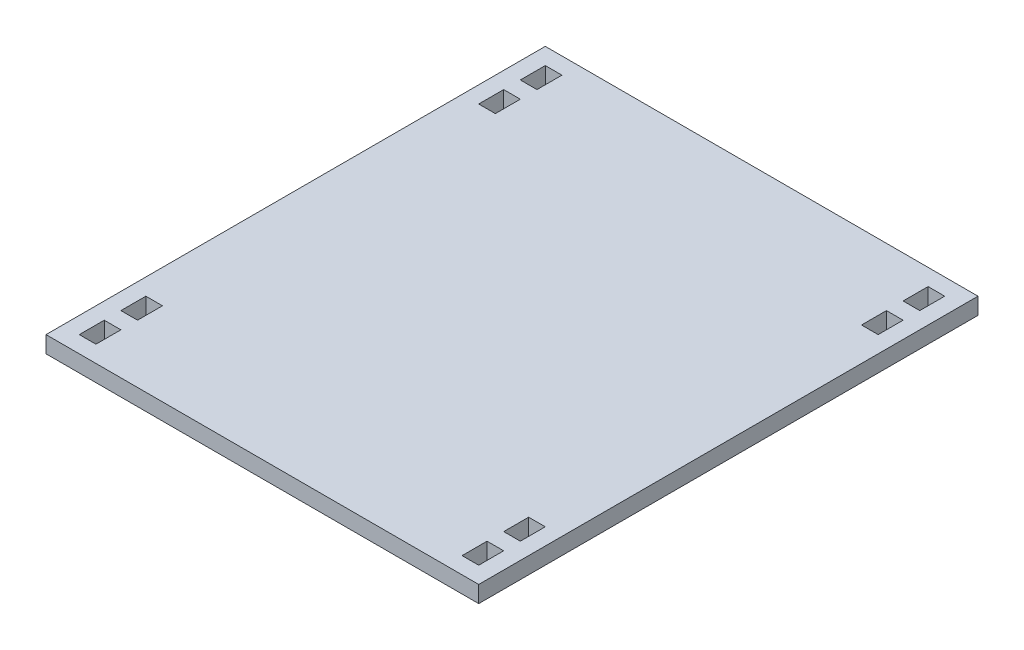
SolidWorks part; units mm, degrees
ref_plane "Front Plane" through (0, 0, 0) normal (0, 0, 1) x (1, 0, 0)
ref_plane "Top Plane" through (0, 0, 0) normal (0, 1, 0) x (1, 0, 0)
ref_plane "Right Plane" through (0, 0, 0) normal (1, 0, 0) x (0, 0, -1)
sketch "Sketch1" plane through (0, 0, 0) normal (0, 1, 0) x (1, 0, 0)
  line L1 (41.275, -47.625) -> (-41.275, -47.625)
  line L2 (41.275, -47.625) -> (41.275, 47.625)
  line L3 (41.275, 47.625) -> (-41.275, 47.625)
  line L4 (-41.275, -47.625) -> (-41.275, 47.625)
  line L5 (41.275, -47.625) -> (-41.275, 47.625) construction
  line L6 (41.275, 47.625) -> (-41.275, -47.625) construction
  point P0 (0, 0)
  dimension "D1" = 82.55
  dimension "D2" = 95.25
extrude "Boss-Extrude1" add sketch "Sketch1" along normal blind 3.175
sketch "Sketch2" plane through (0, 3.175, 0) normal (0, 1, 0) x (1, 0, 0)
  line L0 (-38.1, 39.6875) -> (-38.1, 44.45)
  line L1 (-34.925, 36.5125) -> (-38.1, 36.5125)
  line L2 (-34.925, 36.5125) -> (-34.925, 39.6875) construction
  line L3 (-34.925, 39.6875) -> (-38.1, 39.6875)
  line L4 (-38.1, 36.5125) -> (-38.1, 39.6875) construction
  line L5 (-34.925, 36.5125) -> (-38.1, 39.6875) construction
  line L6 (-34.925, 39.6875) -> (-38.1, 36.5125) construction
  line L7 (-38.1, 44.45) -> (-34.925, 44.45)
  line L8 (-34.925, 44.45) -> (-34.925, 39.6875)
  line L9 (-34.925, 36.5125) -> (-34.925, 31.75)
  line L10 (-34.925, 31.75) -> (-38.1, 31.75)
  line L11 (-38.1, 31.75) -> (-38.1, 36.5125)
  line L12 (-41.275, 47.625) -> (-41.275, -47.625) construction
  line L13 (41.275, 47.625) -> (-41.275, 47.625) construction
  point P0 (-36.5125, 38.1)
  dimension "D1" = 3.175
  dimension "D2" = 3.175
  dimension "D3" = 4.7625
  dimension "D4" = 3.175
  dimension "D5" = 3.175
extrude "Cut-Extrude1" cut sketch "Sketch2" against normal through all contours L11 L1 L9 L10 | L8 L3 L0 L7
pattern_linear "LPattern1" count 2 spacing 76.2 along (0, 0, 1) count 2 spacing 73.025 along (1, 0, 0) of "Cut-Extrude1"
sketch "Sketch3" plane through (0, 0, 0) normal (0, -1, 0) x (1, 0, 0)
  line L8 (-41.3512, 47.7012) -> (-41.3512, -47.7012)
  line L9 (-41.3512, -47.7012) -> (41.3512, -47.7012)
  line L10 (41.3512, -47.7012) -> (41.3512, 47.7012)
  line L11 (41.3512, 47.7012) -> (-41.3512, 47.7012)
  line L12 (-41.3512, 47.7012) -> (-41.3512, -47.7012)
  line L13 (-41.3512, -47.7012) -> (41.3512, -47.7012)
  line L14 (41.3512, -47.7012) -> (41.3512, 47.7012)
  line L15 (41.3512, 47.7012) -> (-41.3512, 47.7012)
  line L20 (35.0012, -36.4363) -> (38.0238, -36.4363)
  line L21 (35.0012, -31.8262) -> (35.0012, -36.4363)
  line L22 (38.0238, -31.8262) -> (35.0012, -31.8262)
  line L23 (38.0238, -36.4363) -> (38.0238, -31.8262)
  line L24 (35.0012, -36.4363) -> (38.0238, -36.4363)
  line L25 (35.0012, -31.8262) -> (35.0012, -36.4363)
  line L26 (38.0238, -31.8262) -> (35.0012, -31.8262)
  line L27 (38.0238, -36.4363) -> (38.0238, -31.8262)
  line L32 (35.0012, -44.3738) -> (38.0238, -44.3738)
  line L33 (38.0238, -44.3738) -> (38.0238, -39.7637)
  line L34 (38.0238, -39.7637) -> (35.0012, -39.7637)
  line L35 (35.0012, -39.7637) -> (35.0012, -44.3738)
  line L36 (35.0012, -44.3738) -> (38.0238, -44.3738)
  line L37 (38.0238, -44.3738) -> (38.0238, -39.7637)
  line L38 (38.0238, -39.7637) -> (35.0012, -39.7637)
  line L39 (35.0012, -39.7637) -> (35.0012, -44.3738)
  line L44 (35.0012, 39.7637) -> (38.0238, 39.7637)
  line L45 (38.0238, 39.7637) -> (38.0238, 44.3738)
  line L46 (38.0238, 44.3738) -> (35.0012, 44.3738)
  line L47 (35.0012, 44.3738) -> (35.0012, 39.7637)
  line L48 (35.0012, 39.7637) -> (38.0238, 39.7637)
  line L49 (38.0238, 39.7637) -> (38.0238, 44.3738)
  line L50 (38.0238, 44.3738) -> (35.0012, 44.3738)
  line L51 (35.0012, 44.3738) -> (35.0012, 39.7637)
  line L56 (35.0012, 31.8262) -> (38.0238, 31.8262)
  line L57 (35.0012, 36.4363) -> (35.0012, 31.8262)
  line L58 (38.0238, 36.4363) -> (35.0012, 36.4363)
  line L59 (38.0238, 31.8262) -> (38.0238, 36.4363)
  line L60 (35.0012, 31.8262) -> (38.0238, 31.8262)
  line L61 (35.0012, 36.4363) -> (35.0012, 31.8262)
  line L62 (38.0238, 36.4363) -> (35.0012, 36.4363)
  line L63 (38.0238, 31.8262) -> (38.0238, 36.4363)
  line L68 (-35.0012, -31.8262) -> (-38.0238, -31.8262)
  line L69 (-35.0012, -36.4363) -> (-35.0012, -31.8262)
  line L70 (-38.0238, -36.4363) -> (-35.0012, -36.4363)
  line L71 (-38.0238, -31.8262) -> (-38.0238, -36.4363)
  line L72 (-35.0012, -31.8262) -> (-38.0238, -31.8262)
  line L73 (-35.0012, -36.4363) -> (-35.0012, -31.8262)
  line L74 (-38.0238, -36.4363) -> (-35.0012, -36.4363)
  line L75 (-38.0238, -31.8262) -> (-38.0238, -36.4363)
  line L80 (-38.0238, -44.3738) -> (-35.0012, -44.3738)
  line L81 (-35.0012, -44.3738) -> (-35.0012, -39.7637)
  line L82 (-35.0012, -39.7637) -> (-38.0238, -39.7637)
  line L83 (-38.0238, -39.7637) -> (-38.0238, -44.3738)
  line L84 (-38.0238, -44.3738) -> (-35.0012, -44.3738)
  line L85 (-35.0012, -44.3738) -> (-35.0012, -39.7637)
  line L86 (-35.0012, -39.7637) -> (-38.0238, -39.7637)
  line L87 (-38.0238, -39.7637) -> (-38.0238, -44.3738)
  line L92 (-38.0238, 39.7637) -> (-35.0012, 39.7637)
  line L93 (-38.0238, 44.3738) -> (-38.0238, 39.7637)
  line L94 (-35.0012, 44.3738) -> (-38.0238, 44.3738)
  line L95 (-35.0012, 39.7637) -> (-35.0012, 44.3738)
  line L96 (-38.0238, 39.7637) -> (-35.0012, 39.7637)
  line L97 (-38.0238, 44.3738) -> (-38.0238, 39.7637)
  line L98 (-35.0012, 44.3738) -> (-38.0238, 44.3738)
  line L99 (-35.0012, 39.7637) -> (-35.0012, 44.3738)
  line L104 (-38.0238, 31.8262) -> (-35.0012, 31.8262)
  line L105 (-35.0012, 31.8262) -> (-35.0012, 36.4363)
  line L106 (-35.0012, 36.4363) -> (-38.0238, 36.4363)
  line L107 (-38.0238, 36.4363) -> (-38.0238, 31.8262)
  line L108 (-38.0238, 31.8262) -> (-35.0012, 31.8262)
  line L109 (-35.0012, 31.8262) -> (-35.0012, 36.4363)
  line L110 (-35.0012, 36.4363) -> (-38.0238, 36.4363)
  line L111 (-38.0238, 36.4363) -> (-38.0238, 31.8262)
  dimension "D1" = 0.0762
  dimension "D2" = 0.0762
  dimension "D3" = 0.0762
  dimension "D4" = 0.0762
  dimension "D5" = 0.0762
  dimension "D6" = 0.0762
  dimension "D7" = 0.0762
  dimension "D8" = 0.0762
  dimension "D9" = 0.0762
